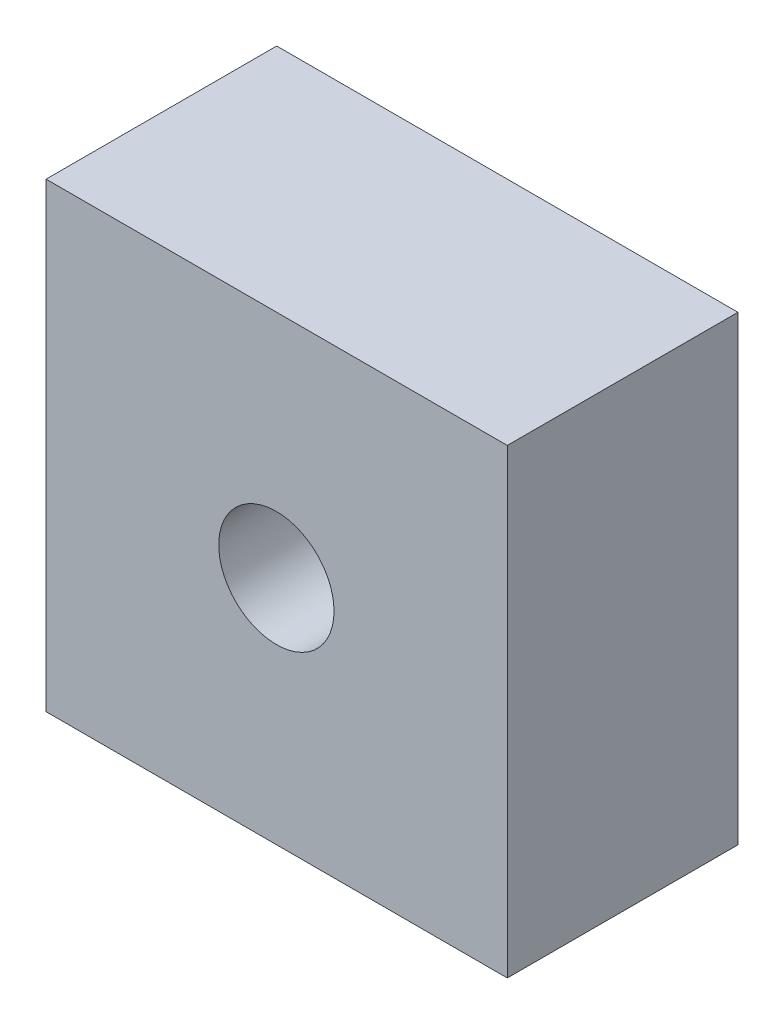
SolidWorks part; units mm, degrees
ref_plane "前视基准面" through (0, 0, 0) normal (0, 0, 1) x (1, 0, 0)
ref_plane "上视基准面" through (0, 0, 0) normal (0, 1, 0) x (1, 0, 0)
ref_plane "右视基准面" through (0, 0, 0) normal (1, 0, 0) x (0, 0, -1)
other "Configuration Table"
sketch "草图1" plane through (0, 0, 0) normal (0, 0, 1) x (1, 0, 0)
  line L1 (0, 0) -> (20, 0)
  line L2 (0, 0) -> (0, 20)
  line L3 (0, 20) -> (20, 20)
  line L4 (20, 0) -> (20, 20)
extrude "BaseBox" add sketch "草图1" along normal blind 10
hole_wizard "孔1" positions "草图3" profile "草图2" legacy
sketch "草图3" plane through (0, 0, 10) normal (0, 0, 1) x (1, 0, 0)
  point P0 (9.9865, 10.0143)
sketch "草图2" plane through (9.9865, 10.0143, 10) normal (1, 0, 0) x (0, -1, 0)
  line L0 (0, 0) -> (0, 15)
  line L1 (0, 15) -> (2.5, 15)
  line L2 (2.5, 15) -> (2.5, 0)
  line L3 (2.5, 0) -> (0, 0)
  line L4 (0, 110) -> (0, -10) construction
  dimension "直径" = 5
  dimension "深度" = 15
